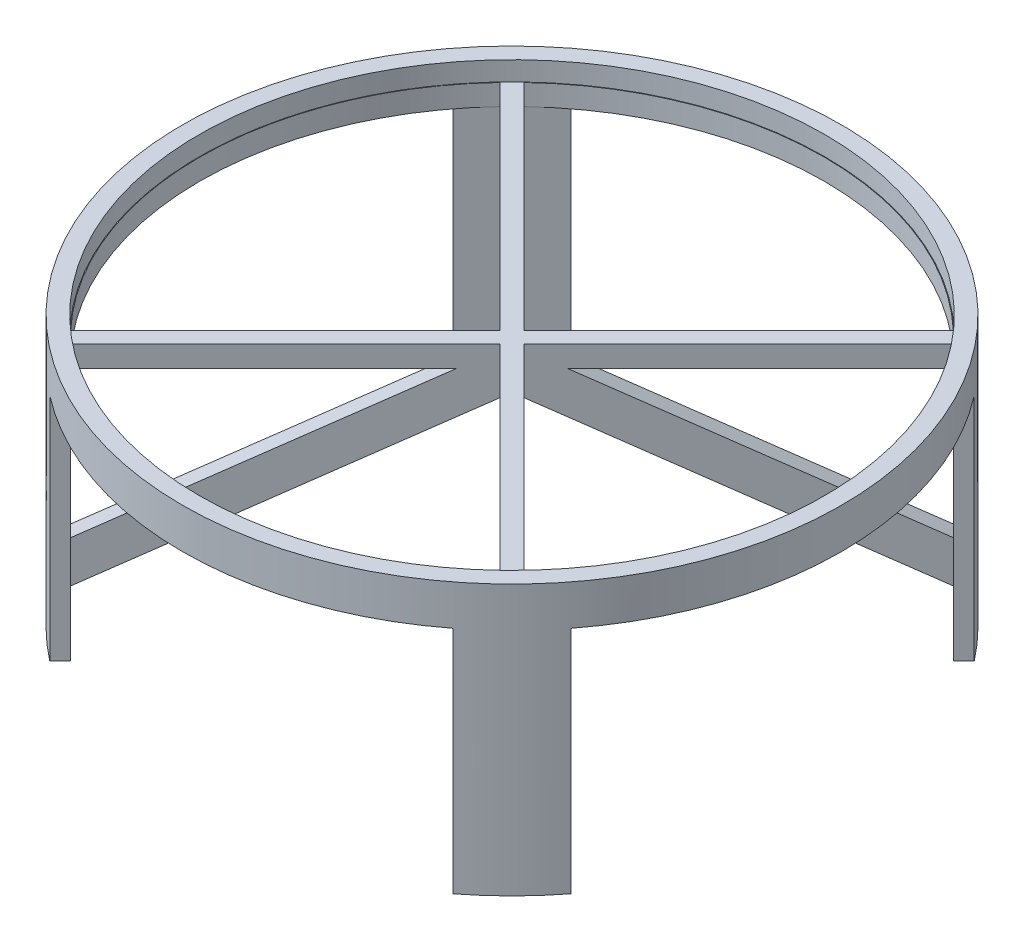
SolidWorks part; units mm, degrees
ref_plane "Front Plane" through (0, 0, 0) normal (0, 0, 1) x (1, 0, 0)
ref_plane "Top Plane" through (0, 0, 0) normal (0, 1, 0) x (1, 0, 0)
ref_plane "Right Plane" through (0, 0, 0) normal (1, 0, 0) x (0, 0, -1)
sketch "Sketch1" plane through (0, 0, 0) normal (0, 1, 0) x (1, 0, 0)
  circle A0 centre (0, 0) radius 100
  dimension "D1" = 200
extrude "Boss-Extrude1" add sketch "Sketch1" along normal blind 6.35
sketch "Sketch2" plane through (0, 6.35, 0) normal (0, 1, 0) x (1, 0, 0)
  line L0 (0, 0) -> (70.7107, -70.7107) construction
  line L3 (79.1184, -79.1184) -> (88.0986, -70.1381)
  line L4 (79.1184, -61.1579) -> (88.0986, -70.1381)
  line L7 (79.1184, -79.1184) -> (70.1381, -88.0986)
  line L8 (61.1579, -79.1184) -> (70.1381, -88.0986)
  line L9 (0, 0) -> (0, -88.3533) construction
  line L10 (-79.1184, -79.1184) -> (-70.1381, -88.0986)
  line L11 (-79.1184, -79.1184) -> (-88.0986, -70.1381)
  line L12 (-61.1579, -79.1184) -> (-70.1381, -88.0986)
  line L13 (-79.1184, -61.1579) -> (-88.0986, -70.1381)
  line L14 (-79.1184, 79.1184) -> (-88.0986, 70.1381)
  line L15 (-79.1184, 79.1184) -> (-70.1381, 88.0986)
  line L16 (-79.1184, 61.1579) -> (-88.0986, 70.1381)
  line L17 (-61.1579, 79.1184) -> (-70.1381, 88.0986)
  line L18 (79.1184, 79.1184) -> (70.1381, 88.0986)
  line L19 (79.1184, 79.1184) -> (88.0986, 70.1381)
  line L20 (61.1579, 79.1184) -> (70.1381, 88.0986)
  line L21 (79.1184, 61.1579) -> (88.0986, 70.1381)
  circle A0 centre (0, 0) radius 100 construction
  arc A1 (61.1579, -79.1184) -> (79.1184, -61.1579) centre (0, 0) ccw construction
  arc A2 (61.1579, -79.1184) -> (79.1184, -61.1579) centre (0, 0) ccw
  arc A3 (61.1579, -79.1184) -> (79.1184, -61.1579) centre (0, 0) ccw
  arc A4 (-79.1184, -61.1579) -> (-61.1579, -79.1184) centre (0, 0) ccw
  arc A5 (-61.1579, 79.1184) -> (-79.1184, 61.1579) centre (0, 0) ccw
  arc A6 (79.1184, 61.1579) -> (61.1579, 79.1184) centre (0, 0) ccw
  point P27 (0, 0)
  circle M12 centre (0, 0) radius 100
  dimension "D1" = 12.7
  dimension "D2" = 25.4
  dimension "D3" = 12.7
  dimension "D4" = 45
  dimension "D5" = 4
extrude "Boss-Extrude2" add sketch "Sketch2" along normal blind 14.986 and the other way blind 76.1288 contours L8 L7 L3 L4 M12 | L21 L19 L18 L20 M12 | L17 L15 L14 L16 M12 | L13 L11 L10 L12 A4
sketch "Sketch3" plane through (0, 6.35, 0) normal (0, 1, 0) x (1, 0, 0)
  circle A0 centre (0, 0) radius 100
  circle A1 centre (0, 0) radius 94.92
  arc A2 (-79.1184, 61.1579) -> (-79.1184, -61.1579) centre (0, 0) ccw construction
  dimension "D1" = 5.08
extrude "Boss-Extrude3" add sketch "Sketch3" along normal blind 5.842
sketch3d "3DSketch3"
  line L0 (0, 0, 0) -> (-70.1381, -53.2688, -70.1381)
  line L1 (-61.1579, -53.2688, -79.1184) -> (-79.1184, -53.2688, -61.1579) construction
  line L3 (-79.1184, -69.7788, -61.1579) -> (-79.1184, 0, -61.1579) construction
  line L4 (-61.1579, -69.7788, -79.1184) -> (-79.1184, -69.7788, -61.1579) construction
  line L5 (-68.3421, -59.6188, -71.9342) -> (-71.9342, -59.6188, -68.3421) construction
  line L6 (-68.3421, -59.6188, -71.9342) -> (-68.3421, -46.9188, -71.9342) construction
  line L7 (-68.3421, -46.9188, -71.9342) -> (-71.9342, -46.9188, -68.3421) construction
  line L8 (-71.9342, -59.6188, -68.3421) -> (-71.9342, -46.9188, -68.3421) construction
  line L9 (-68.3421, -59.6188, -71.9342) -> (-71.9342, -46.9188, -68.3421) construction
  line L10 (-68.3421, -46.9188, -71.9342) -> (-71.9342, -59.6188, -68.3421) construction
  line L11 (-61.1579, -69.7788, -79.1184) -> (-61.1579, 0, -79.1184) construction
  point P15 (-70.1381, -53.2688, -70.1381)
  dimension "D1" = 12.7
  dimension "D2" = 5.08
  dimension "D3" = 16.51
sketch3d "3DSketch4"
  line L0 (-68.3421, -59.6188, -71.9342) -> (-71.9342, -59.6188, -68.3421) construction
  line L1 (-68.3421, -59.6188, -71.9342) -> (-71.9342, -59.6188, -68.3421)
  line L2 (-68.3421, -59.6188, -71.9342) -> (-68.3421, -46.9188, -71.9342)
  line L3 (-68.3421, -46.9188, -71.9342) -> (-71.9342, -46.9188, -68.3421)
  line L4 (-71.9342, -59.6188, -68.3421) -> (-71.9342, -46.9188, -68.3421)
  line L5 (-68.3421, -59.6188, -71.9342) -> (-71.9342, -46.9188, -68.3421) construction
  line L6 (-68.3421, -46.9188, -71.9342) -> (-71.9342, -59.6188, -68.3421) construction
  point P0 (-70.1381, -53.2688, -70.1381)
sweep "Sweep1" add profiles "3DSketch4" path "3DSketch3"
pattern_circular "CirPattern1" count 4 over 360 about axis through (0, 0, 0) along (0, 1, 0) of "Sweep1"
sketch "Sketch29" plane through (70.1381, 0, 70.1381) normal (0.7071, 0, 0.7071) x (0.7071, 0, -0.7071)
  line L4 (2.54, -59.6188) -> (2.54, -46.9188)
  line L5 (2.54, -46.9188) -> (-2.54, -46.9188)
  line L6 (-2.54, -46.9188) -> (-2.54, -59.6188)
  line L7 (-2.54, -59.6188) -> (2.54, -59.6188)
  line L8 (2.54, -59.6188) -> (2.54, -46.9188)
  line L9 (2.54, -46.9188) -> (-2.54, -46.9188)
  line L10 (-2.54, -46.9188) -> (-2.54, -59.6188)
  line L11 (-2.54, -59.6188) -> (2.54, -59.6188)
  dimension "D1" = 0
extrude "Boss-Extrude4" add sketch "Sketch29" along normal blind 6.35
pattern_circular "CirPattern2" count 4 over 360 about axis through (0, 0, 0) along (0, 1, 0) of "Boss-Extrude4"
sketch "Sketch30" plane through (0, 6.35, 0) normal (0, 1, 0) x (1, 0, 0)
  line L0 (-10.157, -6.5649) -> (-71.9342, -68.3421) construction
  line L1 (-6.5649, -10.157) -> (-68.3421, -71.9342) construction
  line L2 (-10.157, -6.5649) -> (-68.7643, -65.1722)
  line L3 (-6.5649, -10.157) -> (-65.1722, -68.7643)
  line L4 (-6.5649, 10.157) -> (-68.3421, 71.9342) construction
  line L5 (-10.157, 6.5649) -> (-71.9342, 68.3421) construction
  line L6 (6.5649, 10.157) -> (68.3421, 71.9342) construction
  line L7 (10.157, 6.5649) -> (71.9342, 68.3421) construction
  line L8 (10.157, -6.5649) -> (71.9342, -68.3421) construction
  line L9 (6.5649, -10.157) -> (68.3421, -71.9342) construction
  line L10 (-6.5649, 10.157) -> (-65.1722, 68.7643)
  line L11 (-10.157, 6.5649) -> (-68.7643, 65.1722)
  line L12 (6.5649, 10.157) -> (65.1722, 68.7643)
  line L13 (10.157, 6.5649) -> (68.7643, 65.1722)
  line L14 (10.157, -6.5649) -> (68.7643, -65.1722)
  line L15 (6.5649, -10.157) -> (65.1722, -68.7643)
  line L16 (-6.5649, -10.157) -> (0, -3.5921)
  line L17 (-10.157, -6.5649) -> (-3.5921, 0)
  line L18 (-6.5649, 10.157) -> (0, 3.5921)
  line L19 (6.5649, -10.157) -> (0, -3.5921)
  line L20 (-3.5921, 0) -> (-10.157, 6.5649)
  line L21 (3.5921, 0) -> (10.157, -6.5649)
  line L22 (3.5921, 0) -> (10.157, 6.5649)
  line L23 (0, 3.5921) -> (6.5649, 10.157)
  arc A0 (68.7643, -65.1722) -> (68.7643, 65.1722) centre (0, 0) ccw
  arc A1 (65.1722, 68.7643) -> (-65.1722, 68.7643) centre (0, 0) ccw
  arc A2 (-68.7643, 65.1722) -> (-68.7643, -65.1722) centre (0, 0) ccw
  arc A3 (-65.1722, -68.7643) -> (65.1722, -68.7643) centre (0, 0) ccw
  circle M1 centre (0, 0) radius 94.92
extrude "Cut-Extrude3" cut sketch "Sketch30" against normal blind 6.35 contours L18 L23 L12 L10 M1 | L22 L21 L14 L13 M1 | L15 L19 L16 L3 M1 | L11 A2 L2 L17 L20
sketch "Sketch32" plane through (0, 21.336, 0) normal (0, 1, 0) x (1, 0, 0)
  line L3 (79.1184, 61.1579) -> (88.0986, 70.1381)
  line L4 (88.0986, 70.1381) -> (70.1381, 88.0986)
  line L5 (70.1381, 88.0986) -> (61.1579, 79.1184)
  line L6 (79.1184, 61.1579) -> (88.0986, 70.1381)
  line L7 (88.0986, 70.1381) -> (70.1381, 88.0986)
  line L8 (70.1381, 88.0986) -> (61.1579, 79.1184)
  arc A1 (79.1184, 61.1579) -> (61.1579, 79.1184) centre (0, 0) ccw
  arc A2 (79.1184, 61.1579) -> (61.1579, 79.1184) centre (0, 0) ccw
  dimension "D1" = 0
extrude "Cut-Extrude4" cut sketch "Sketch32" against normal up to vertex (9.144 mm away)
pattern_circular "CirPattern3" count 4 over 360 about axis through (0, 12.192, 0) along (0, -1, 0) of "Cut-Extrude4"
ref_plane "Plane1" through (0, 0, 0) normal (0.7071, 0, -0.7071) x (-0.7071, 0, -0.7071)
sketch "Sketch33" plane through (0, 0, 0) normal (0.7071, 0, -0.7071) x (-0.7071, 0, -0.7071)
  line L0 (-94.7074, 0) -> (-94.7074, -49.9415)
  line L3 (-100, -69.7788) -> (-94.7074, -69.7788)
  line L4 (-94.7074, 0) -> (-100, 0)
  line L5 (-100, 0) -> (-100, -46.9188) construction
  line L6 (-100, 0) -> (-100, -69.7788)
  line L7 (-100, 0) -> (-100, -46.9188) construction
  line L8 (-100, 0) -> (-100, -46.9188)
  line L10 (-94.7074, -63.9486) -> (-94.7074, -69.7788)
  line L11 (-94.7074, -49.9415) -> (-94.7074, -63.9486) construction
  line L12 (-100, -46.9188) -> (-100, 0)
  line L13 (-94.7074, -49.9415) -> (-94.7074, -63.9486)
  line L14 (-94.7074, -49.9415) -> (-94.7074, -63.9486)
  line L15 (-100, -69.7788) -> (-99.1903, -69.7788) construction
  line L16 (-100, 0) -> (-94.7074, 0)
  line L17 (-100, 0) -> (-100, -69.7788)
  line L19 (-100, -69.7788) -> (-94.7074, -69.7788)
  line L22 (-94.7074, 0) -> (-94.7074, -69.7788)
  line L23 (-100, -69.7788) -> (-99.1903, -69.7788)
  line L24 (-100, -69.7788) -> (-100, -46.9188)
extrude "Boss-Extrude6" add sketch "Sketch33" along normal blind 12.7 and the other way blind 12.7
pattern_circular "CirPattern4" count 4 over 360 about axis through (0, 0, 0) along (0, 1, 0) of "Boss-Extrude6"
sketch "Sketch34" plane through (79.1184, 0, 79.1184) normal (0.7071, 0, 0.7071) x (0.7071, 0, -0.7071)
  line L0 (-12.7, -69.7788) -> (-12.7, 12.192) construction
  line L1 (-12.7, 12.192) -> (12.7, 12.192)
  line L2 (-12.7, 12.192) -> (-12.7, -120.65)
  line L3 (-12.7, -120.65) -> (12.7, -120.65)
  line L4 (12.7, 12.192) -> (12.7, -120.65)
  line L5 (-12.7, 12.192) -> (12.7, 12.192) construction
  line L6 (12.7, -69.7788) -> (12.7, 12.192) construction
extrude "Cut-Extrude5" cut sketch "Sketch34" against normal blind 7.62
pattern_circular "CirPattern5" count 4 over 360 about axis through (0, 0, 0) along (0, 1, 0) of "Cut-Extrude5"
sketch "Sketch35" plane through (0, 12.192, 0) normal (0, 1, 0) x (1, 0, 0)
  line L0 (-61.1579, 79.1184) -> (-64.75, 82.7105) construction
  line L1 (-82.7105, 64.75) -> (-79.1184, 61.1579) construction
  line L2 (-82.7105, 64.75) -> (-64.75, 82.7105) construction
  line L3 (-61.1579, 79.1184) -> (-64.75, 82.7105)
  line L4 (-82.7105, 64.75) -> (-79.1184, 61.1579)
  line L5 (-82.7105, 64.75) -> (-64.75, 82.7105)
  line L6 (-64.75, -82.7105) -> (-61.1579, -79.1184) construction
  line L7 (-64.75, -82.7105) -> (-82.7105, -64.75) construction
  line L8 (-79.1184, -61.1579) -> (-82.7105, -64.75) construction
  line L9 (61.1579, -79.1184) -> (64.75, -82.7105) construction
  line L10 (82.7105, -64.75) -> (64.75, -82.7105) construction
  line L11 (82.7105, -64.75) -> (79.1184, -61.1579) construction
  line L12 (79.1184, 61.1579) -> (82.7105, 64.75) construction
  line L13 (64.75, 82.7105) -> (82.7105, 64.75) construction
  line L14 (64.75, 82.7105) -> (61.1579, 79.1184) construction
  line L15 (-64.75, -82.7105) -> (-61.1579, -79.1184)
  line L16 (-64.75, -82.7105) -> (-82.7105, -64.75)
  line L17 (-79.1184, -61.1579) -> (-82.7105, -64.75)
  line L18 (61.1579, -79.1184) -> (64.75, -82.7105)
  line L19 (82.7105, -64.75) -> (64.75, -82.7105)
  line L20 (82.7105, -64.75) -> (79.1184, -61.1579)
  line L21 (79.1184, 61.1579) -> (82.7105, 64.75)
  line L22 (64.75, 82.7105) -> (82.7105, 64.75)
  line L23 (64.75, 82.7105) -> (61.1579, 79.1184)
  arc A0 (-61.1579, 79.1184) -> (-79.1184, 61.1579) centre (0, 0) ccw
  arc A1 (-79.1184, -61.1579) -> (-61.1579, -79.1184) centre (0, 0) ccw
  arc A2 (61.1579, -79.1184) -> (79.1184, -61.1579) centre (0, 0) ccw
  arc A3 (79.1184, 61.1579) -> (61.1579, 79.1184) centre (0, 0) ccw
extrude "Cut-Extrude6" cut sketch "Sketch35" against normal blind 88.9
